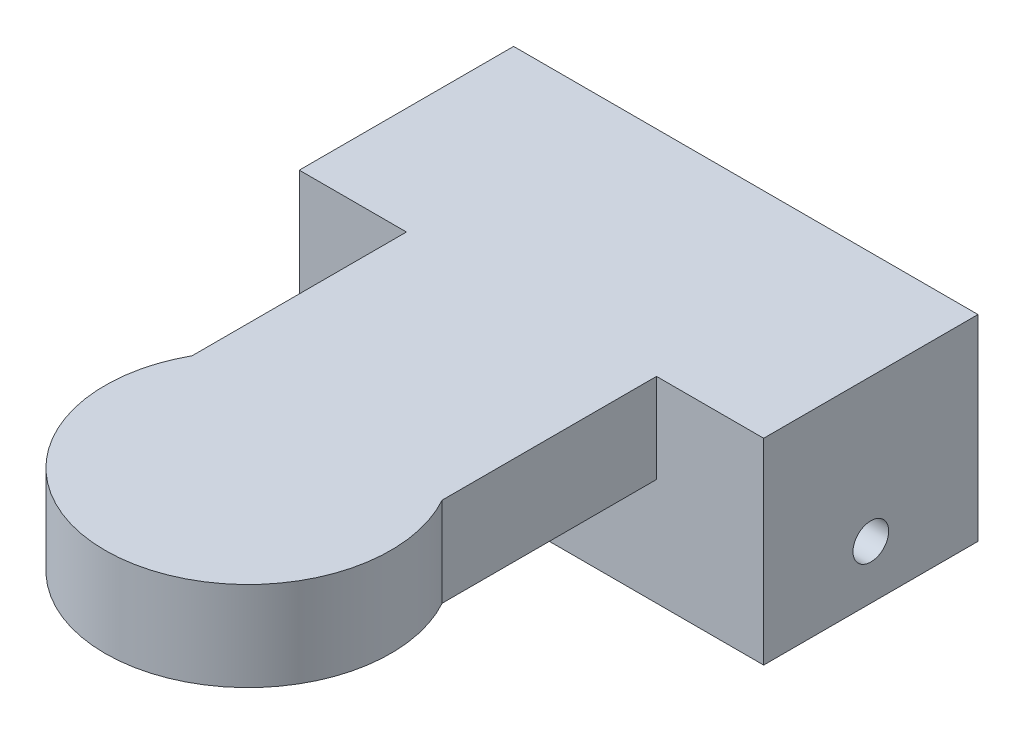
SolidWorks part; units mm, degrees
ref_plane "Front Plane" through (0, 0, 0) normal (0, 0, 1) x (1, 0, 0)
ref_plane "Top Plane" through (0, 0, 0) normal (0, 1, 0) x (1, 0, 0)
ref_plane "Right Plane" through (0, 0, 0) normal (1, 0, 0) x (0, 0, -1)
sketch "Sketch1" plane through (0, 0, 0) normal (0, 1, 0) x (1, 0, 0)
  circle A21 centre (0, 0) radius 20
  dimension "D1" = 40
extrude "Boss-Extrude1" add sketch "Sketch1" along normal blind 10
sketch "Sketch2" plane through (0, 10, 0) normal (0, 1, 0) x (1, 0, 0)
  line L6 (-1.9621, 3.6) -> (1.9621, 3.6)
  line L7 (3.6, 1.9621) -> (3.6, -1.9621)
  arc A3 (-0.6789, -4.0434) -> (3.6, -1.9621) centre (0, 0) ccw
  arc A4 (-1.9621, 3.6) -> (-4.0434, -0.6789) centre (0, 0) ccw
  arc A5 (-4.0434, -0.6789) -> (-0.6789, -4.0434) centre (0, 0) ccw
  arc A6 (3.6, 1.9621) -> (1.9621, 3.6) centre (0, 0) ccw
  point P19 (0, 3.6)
  dimension "D1" = 3.9243
  dimension "D4" = 4.1
  dimension "D6" = 3.9243
extrude "Cut-Extrude1" cut sketch "Sketch2" against normal through all
sketch "Sketch3" plane through (0, 0, 0) normal (0, 1, 0) x (1, 0, 0)
  line L0 (-17.5, 59.6825) -> (-17.5, 9.6825)
  line L1 (-17.5, 59.6825) -> (17.5, 59.6825)
  line L2 (17.5, 59.6825) -> (17.5, 9.6825)
  circle A0 centre (0, 0) radius 20 construction
  arc A1 (17.5, 9.6825) -> (-17.5, 9.6825) centre (0, 0) ccw
  point P6 (0, 59.6825)
  dimension "D1" = 35
  dimension "D2" = 50
extrude "Boss-Extrude2" add sketch "Sketch3" along normal up to surface (10 mm away) up to face at (0, 10, 20)
sketch "Sketch5" plane through (0, 0, 0) normal (0, -1, 0) x (1, 0, 0)
  line L7 (3.6, 1.9621) -> (3.6, -1.9621)
  line L8 (-1.9621, -3.6) -> (1.9621, -3.6)
  circle A0 centre (0, 0) radius 12.5
  arc A6 (1.9621, -3.6) -> (3.6, -1.9621) centre (0, 0) ccw
  arc A7 (3.6, 1.9621) -> (-1.9621, -3.6) centre (0, 0) ccw
  dimension "D1" = 25
extrude "Boss-Extrude3" add sketch "Sketch5" along normal blind 6
sketch "Sketch6" plane through (0, 0, -59.6825) normal (0, 0, -1) x (-1, 0, 0)
  line L0 (-32.5, 10) -> (32.5, 10)
  line L1 (-32.5, 10) -> (-32.5, -15)
  line L2 (-32.5, -15) -> (-22.5, -15)
  line L3 (-22.5, -15) -> (-22.5, 0)
  line L4 (-22.5, 0) -> (22.5, 0)
  line L5 (22.5, 0) -> (22.5, -15)
  line L6 (22.5, -15) -> (32.5, -15)
  line L7 (32.5, -15) -> (32.5, 10)
  line L8 (-17.5, 10) -> (17.5, 10) construction
  line L9 (-17.5, 0) -> (17.5, 0) construction
  point P10 (0, 0)
  dimension "D1" = 45
  dimension "D2" = 10
  dimension "D3" = 15
extrude "Boss-Extrude4" add sketch "Sketch6" against normal blind 20 and the other way blind 10
sketch "Sketch7" plane through (32.5, 0, 0) normal (1, 0, 0) x (0, 0, -1)
  line L0 (39.6825, -15) -> (69.6825, -15) construction
  line L1 (9.6825, 0) -> (39.6825, 0) construction
  circle A0 centre (54.6825, -7.5) radius 2.5
  point P4 (54.6825, -15)
  dimension "D2" = 5
  dimension "D1" = 7.5
extrude "Cut-Extrude2" cut sketch "Sketch7" against normal through all
sketch "Sketch8" plane through (0, 10, 0) normal (0, 1, 0) x (1, 0, 0)
  line L0 (-32.5, 39.6825) -> (-32.5, 69.6825) construction
  line L2 (-32.5, 69.6825) -> (-32.5, 39.6825)
  line L3 (-32.5, 39.6825) -> (-17.5, 39.6825)
  line L4 (32.5, 69.6825) -> (32.5, 39.6825)
  line L6 (17.5, 39.6825) -> (32.5, 39.6825)
  line L8 (-17.5, 39.6825) -> (-17.5, 9.6825)
  line L10 (17.5, 39.6825) -> (17.5, 9.6825)
  line L11 (-32.5, 69.6825) -> (-32.5, 39.6825) construction
  line L12 (-32.5, 69.6825) -> (32.5, 69.6825) construction
  line L13 (32.5, 69.6825) -> (32.5, 39.6825) construction
  line L14 (32.5, 69.6825) -> (-32.5, 69.6825)
  arc A0 (-17.5, 9.6825) -> (17.5, 9.6825) centre (0, 0) ccw
extrude "Boss-Extrude5" add sketch "Sketch8" along normal blind 2.5
sketch "Sketch9" plane through (0, -6, 0) normal (0, -1, 0) x (1, 0, 0)
  circle A0 centre (0, 0) radius 12.5
  circle A1 centre (0, 0) radius 12.5 construction
extrude "Cut-Extrude3" cut sketch "Sketch9" against normal blind 2.5
sketch "Sketch10" plane through (0, 0, -69.6825) normal (0, 0, -1) x (-1, 0, 0)
  line L1 (-22.5, 0) -> (22.5, 0)
  line L2 (-22.5, 0) -> (-22.5, -15)
  line L3 (-22.5, -15) -> (22.5, -15)
  line L4 (22.5, 0) -> (22.5, -15)
extrude "Boss-Extrude6" add sketch "Sketch10" against normal blind 9.95
sketch "Sketch11" plane through (0, 0, -39.6825) normal (0, 0, 1) x (1, 0, 0)
  line L1 (-22.5, 0) -> (22.5, 0)
  line L2 (-22.5, 0) -> (-22.5, -15)
  line L3 (-22.5, -15) -> (22.5, -15)
  line L4 (22.5, 0) -> (22.5, -15)
extrude "Boss-Extrude7" add sketch "Sketch11" against normal blind 9.95
sketch "Sketch12" plane through (0, 0, -69.6825) normal (0, 0, -1) x (-1, 0, 0)
  circle A0 centre (0, -60) radius 47.5
  dimension "D1" = 95
  dimension "D2" = 60
extrude "Cut-Extrude4" cut sketch "Sketch12" against normal blind 10
